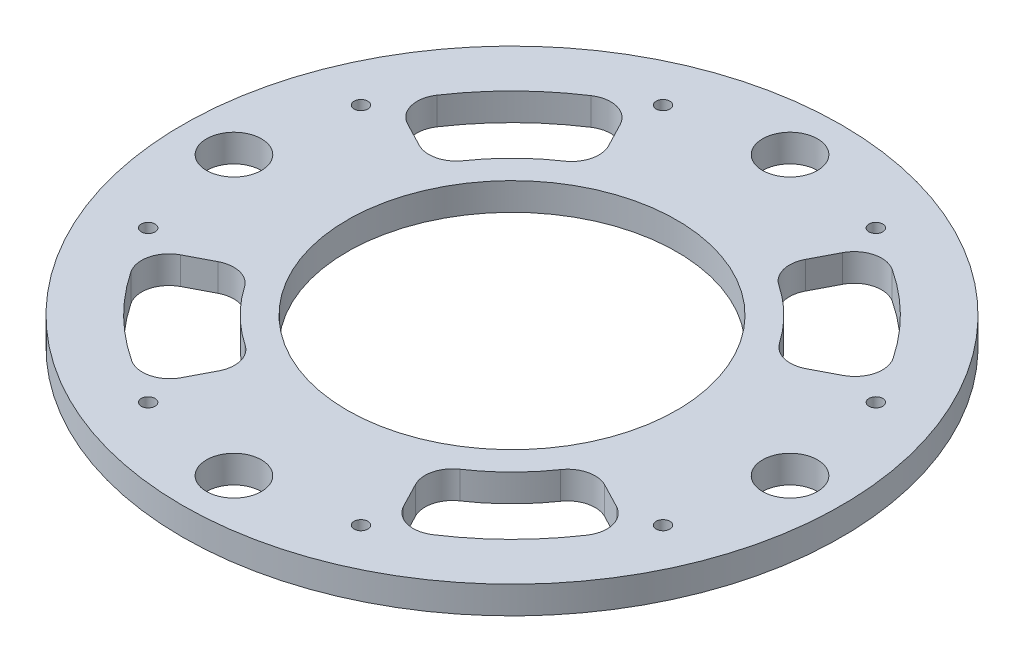
SolidWorks part; units mm, degrees
material "Acrylic (Medium-high impact)"
ref_plane "Front Plane" through (0, 0, 0) normal (0, 0, 1) x (1, 0, 0)
ref_plane "Top Plane" through (0, 0, 0) normal (0, 1, 0) x (1, 0, 0)
ref_plane "Right Plane" through (0, 0, 0) normal (1, 0, 0) x (0, 0, -1)
sketch "Sketch1" plane through (0, 0, 0) normal (0, 1, 0) x (1, 0, 0)
  circle A0 centre (0, 0) radius 76.2
  dimension "D1" = 152.4
extrude "Boss-Extrude1" add sketch "Sketch1" along normal blind 6.35
sketch "Sketch2" plane through (0, 6.35, 0) normal (0, 1, 0) x (1, 0, 0)
  circle A0 centre (0, 0) radius 35
  dimension "D1" = 70
extrude "Cut-Extrude1" cut sketch "Sketch2" against normal blind 6.35
sketch "Sketch3" plane through (0, 6.35, 0) normal (0, 1, 0) x (1, 0, 0)
  line L0 (-76.2, 0) -> (76.2, 0) construction
  line L1 (-51.5875, 51.5875) -> (51.5875, 51.5875) construction
  line L2 (-51.5875, 51.5875) -> (-51.5875, -51.5875) construction
  line L3 (-51.5875, -51.5875) -> (51.5875, -51.5875) construction
  line L4 (51.5875, 51.5875) -> (51.5875, -51.5875) construction
  circle A0 centre (0, 0) radius 76.2 construction
  circle A1 centre (-64.2875, 0) radius 6.35
  circle A2 centre (64.2875, 0) radius 6.35
  dimension "D1" = 12.7
  dimension "D2" = 12.7
  dimension "D3" = 12.7
  dimension "D4" = 12.7
extrude "Cut-Extrude2" cut sketch "Sketch3" against normal blind 10
sketch "Sketch4" plane through (0, 6.35, 0) normal (0, 1, 0) x (1, 0, 0)
  line L1 (50, -50) -> (-50, -50) construction
  line L2 (50, -50) -> (50, 50) construction
  line L3 (50, 50) -> (-50, 50) construction
  line L4 (-50, -50) -> (-50, 50) construction
  line L5 (50, -50) -> (-50, 50) construction
  line L6 (50, 50) -> (-50, -50) construction
  point P0 (0, 0)
  dimension "D1" = 100
  dimension "D2" = 100
sketch "Sketch5" plane through (0, 6.35, 0) normal (0, 1, 0) x (1, 0, 0)
  line L0 (-50, 24.6) -> (-59.525, 24.6) construction
  line L1 (-50, -50) -> (-50, 50) construction
  line L2 (-50, -24.6) -> (-59.525, -24.6) construction
  line L3 (50, 50) -> (-50, 50) construction
  line L4 (50, -50) -> (-50, -50) construction
  line L5 (-50, 50) -> (50, -50) construction
  line L6 (-50, -50) -> (50, 50) construction
  line L7 (24.6, 50) -> (24.6, 59.525) construction
  line L8 (-50, 50) -> (50, 50) construction
  line L9 (-50, 50) -> (-50, -50) construction
  line L10 (-50, -50) -> (50, -50) construction
  line L11 (50, 50) -> (50, -50) construction
  line L12 (-24.6, 50) -> (-24.6, 59.525) construction
  line L13 (50, 24.6) -> (59.525, 24.6) construction
  line L14 (-24.6, -50) -> (-24.6, -59.525) construction
  line L15 (24.6, -50) -> (24.6, -59.525) construction
  line L16 (50, -24.6) -> (59.525, -24.6) construction
  dimension "D1" = 25.4
  dimension "D2" = 25.4
  dimension "D3" = 9.525
  dimension "D4" = 9.525
sketch "Sketch7" plane through (0, 6.35, 0) normal (0, 1, 0) x (1, 0, 0)
  line L0 (0, 0) -> (0, 76.2) construction
  line L1 (0, 0) -> (53.8815, 53.8815) construction
  line L2 (0, 59.5249) -> (-24.5999, 59.5249) construction
  line L3 (0, 0) -> (76.2, 0) construction
  line L4 (0, -59.5249) -> (-24.5999, -59.5249) construction
  circle A0 centre (0, 0) radius 76.2 construction
  circle A1 centre (-24.5999, 59.5249) radius 1.5875
  circle A2 centre (24.5999, 59.5249) radius 1.5875
  circle A3 centre (24.5999, -59.5249) radius 1.5875
  circle A4 centre (-24.5999, -59.5249) radius 1.5875
  circle A5 centre (-59.5249, 24.5999) radius 1.5875
  circle A6 centre (-59.5249, -24.5999) radius 1.5875
  circle A7 centre (59.5249, 24.5999) radius 1.5875
  circle A8 centre (59.5249, -24.5999) radius 1.5875
  dimension "D1" = 45
  dimension "D2" = 59.5249
  dimension "D3" = 24.5999
extrude "Cut-Extrude4" cut sketch "Sketch7" against normal blind 10
sketch "Sketch8" plane through (0, 6.35, 0) normal (0, 1, 0) x (1, 0, 0)
  line L0 (0, 76.2) -> (0, -76.2) construction
  line L1 (0, 0) -> (53.8815, 53.8815) construction
  circle A0 centre (0, 0) radius 76.2 construction
  circle A1 centre (-64.2875, 0) radius 6.35
  circle A2 centre (64.2875, 0) radius 6.35
  circle A3 centre (0, -64.2875) radius 6.35
  circle A4 centre (0, 64.2875) radius 6.35
extrude "Cut-Extrude5" cut sketch "Sketch8" against normal blind 10
sketch "Sketch9" plane through (0, 6.35, 0) normal (0, 1, 0) x (1, 0, 0)
  circle A0 centre (0, 0) radius 38.1
  dimension "D1" = 76.2
extrude "Cut-Extrude6" cut sketch "Sketch9" against normal blind 10
sketch "Sketch10" plane through (0, 6.35, 0) normal (0, 1, 0) x (1, 0, 0)
  line L0 (0, 0) -> (-76.2, 0) construction
  line L1 (0, 0) -> (0, 76.2) construction
  line L2 (0, 0) -> (-53.8815, 53.8815) construction
  line L3 (-22.7447, 45.0673) -> (-25.6934, 50.7318)
  line L4 (-44.7067, 23.2729) -> (-50.3788, 26.2255)
  line L5 (44.7067, 23.2729) -> (50.3788, 26.2255)
  line L6 (22.7447, 45.0673) -> (25.6934, 50.7318)
  line L7 (22.7447, -45.0673) -> (25.6934, -50.7318)
  line L8 (44.7067, -23.2729) -> (50.3788, -26.2255)
  line L9 (-44.7067, -23.2729) -> (-50.3788, -26.2255)
  line L10 (-22.7447, -45.0673) -> (-25.6934, -50.7318)
  circle A0 centre (0, 0) radius 76.2 construction
  arc A1 (-24.83, 36.8683) -> (-36.5528, 25.2922) centre (0, 0) ccw
  arc A2 (-34.8066, 53.1108) -> (-52.7185, 35.3978) centre (0, 0) ccw
  circle A3 centre (0, 0) radius 38.1 construction
  arc A4 (-52.7185, 35.3978) -> (-50.3788, 26.2255) centre (-47.4467, 31.8581) ccw
  arc A5 (-44.7067, 23.2729) -> (-36.5528, 25.2922) centre (-41.7746, 28.9054) ccw
  arc A6 (-24.83, 36.8683) -> (-22.7447, 45.0673) centre (-28.3772, 42.1352) ccw
  arc A7 (-25.6934, 50.7318) -> (-34.8066, 53.1108) centre (-31.3259, 47.7997) ccw
  arc A8 (25.6934, 50.7318) -> (34.8066, 53.1108) centre (31.3259, 47.7997) cw
  arc A9 (24.83, 36.8683) -> (22.7447, 45.0673) centre (28.3772, 42.1352) cw
  arc A10 (44.7067, 23.2729) -> (36.5528, 25.2922) centre (41.7746, 28.9054) cw
  arc A11 (52.7185, 35.3978) -> (50.3788, 26.2255) centre (47.4467, 31.8581) cw
  arc A12 (34.8066, 53.1108) -> (52.7185, 35.3978) centre (0, 0) cw
  arc A13 (24.83, 36.8683) -> (36.5528, 25.2922) centre (0, 0) cw
  arc A14 (24.83, -36.8683) -> (36.5528, -25.2922) centre (0, 0) ccw
  arc A15 (34.8066, -53.1108) -> (52.7185, -35.3978) centre (0, 0) ccw
  arc A16 (52.7185, -35.3978) -> (50.3788, -26.2255) centre (47.4467, -31.8581) ccw
  arc A17 (44.7067, -23.2729) -> (36.5528, -25.2922) centre (41.7746, -28.9054) ccw
  arc A18 (24.83, -36.8683) -> (22.7447, -45.0673) centre (28.3772, -42.1352) ccw
  arc A19 (25.6934, -50.7318) -> (34.8066, -53.1108) centre (31.3259, -47.7997) ccw
  arc A20 (-25.6934, -50.7318) -> (-34.8066, -53.1108) centre (-31.3259, -47.7997) cw
  arc A21 (-24.83, -36.8683) -> (-22.7447, -45.0673) centre (-28.3772, -42.1352) cw
  arc A22 (-44.7067, -23.2729) -> (-36.5528, -25.2922) centre (-41.7746, -28.9054) cw
  arc A23 (-52.7185, -35.3978) -> (-50.3788, -26.2255) centre (-47.4467, -31.8581) cw
  arc A24 (-34.8066, -53.1108) -> (-52.7185, -35.3978) centre (0, 0) cw
  arc A25 (-24.83, -36.8683) -> (-36.5528, -25.2922) centre (0, 0) cw
  circle A26 centre (0, 0) radius 76.2
  dimension "D4" = 6.35
  dimension "D5" = 152.4
  dimension "D6" = 6.35
  dimension "D7" = 12.7
  dimension "D1" = 45
  dimension "D2" = 27.5
  dimension "D3" = 27.5
extrude "Cut-Extrude10" cut sketch "Sketch10" against normal blind 10 contours L3 A7 A2 A4 L4 A5 A1 A6 | A9 A13 A10 L5 A11 A12 A8 L6 | L7 A19 A15 A16 L8 A17 A14 A18 | A21 A25 A22 L9 A23 A24 A20 L10
sketch "Sketch11" plane through (0, 6.35, 0) normal (0, 1, 0) x (1, 0, 0)
  line L0 (-25.6934, 50.7318) -> (-22.7447, 45.0673)
  line L1 (-44.7067, 23.2729) -> (-50.3788, 26.2255)
  line L4 (44.7067, 23.2729) -> (50.3788, 26.2255)
  line L5 (25.6934, 50.7318) -> (22.7447, 45.0673)
  line L6 (25.6934, -50.7318) -> (22.7447, -45.0673)
  line L7 (44.7067, -23.2729) -> (50.3788, -26.2255)
  line L8 (-44.7067, -23.2729) -> (-50.3788, -26.2255)
  line L9 (-25.6934, -50.7318) -> (-22.7447, -45.0673)
  circle A0 centre (0, 0) radius 38.1
  circle A1 centre (0, 0) radius 76.2
  arc A2 (-24.83, 36.8683) -> (-36.5528, 25.2922) centre (0, 0) ccw
  arc A3 (34.8066, 53.1108) -> (52.7185, 35.3978) centre (0, 0) cw
  circle A4 centre (0, 64.2875) radius 6.5947
  circle A5 centre (-64.2875, 0) radius 6.35
  circle A6 centre (-59.5249, 24.5999) radius 1.5875
  circle A7 centre (-24.5999, 59.5249) radius 1.5875
  arc A8 (-50.3788, 26.2255) -> (-52.7185, 35.3978) centre (-47.4467, 31.8581) cw
  arc A9 (-44.7067, 23.2729) -> (-36.5528, 25.2922) centre (-41.7746, 28.9054) ccw
  arc A10 (-22.7447, 45.0673) -> (-24.83, 36.8683) centre (-28.3772, 42.1352) cw
  arc A11 (-25.6934, 50.7318) -> (-34.8066, 53.1108) centre (-31.3259, 47.7997) ccw
  arc A12 (-34.8066, 53.1108) -> (-52.7185, 35.3978) centre (0, 0) ccw
  arc A13 (25.6934, 50.7318) -> (34.8066, 53.1108) centre (31.3259, 47.7997) cw
  arc A14 (22.7447, 45.0673) -> (24.83, 36.8683) centre (28.3772, 42.1352) ccw
  arc A15 (44.7067, 23.2729) -> (36.5528, 25.2922) centre (41.7746, 28.9054) cw
  arc A16 (50.3788, 26.2255) -> (52.7185, 35.3978) centre (47.4467, 31.8581) ccw
  circle A17 centre (24.5999, 59.5249) radius 1.5875
  circle A18 centre (59.5249, 24.5999) radius 1.5875
  circle A19 centre (64.2875, 0) radius 6.35
  arc A20 (24.83, 36.8683) -> (36.5528, 25.2922) centre (0, 0) cw
  arc A21 (24.83, -36.8683) -> (36.5528, -25.2922) centre (0, 0) ccw
  circle A22 centre (59.5249, -24.5999) radius 1.5875
  circle A23 centre (24.5999, -59.5249) radius 1.5875
  arc A24 (50.3788, -26.2255) -> (52.7185, -35.3978) centre (47.4467, -31.8581) cw
  arc A25 (44.7067, -23.2729) -> (36.5528, -25.2922) centre (41.7746, -28.9054) ccw
  arc A26 (22.7447, -45.0673) -> (24.83, -36.8683) centre (28.3772, -42.1352) cw
  arc A27 (25.6934, -50.7318) -> (34.8066, -53.1108) centre (31.3259, -47.7997) ccw
  arc A28 (34.8066, -53.1108) -> (52.7185, -35.3978) centre (0, 0) ccw
  arc A29 (-34.8066, -53.1108) -> (-52.7185, -35.3978) centre (0, 0) cw
  arc A30 (-25.6934, -50.7318) -> (-34.8066, -53.1108) centre (-31.3259, -47.7997) cw
  arc A31 (-22.7447, -45.0673) -> (-24.83, -36.8683) centre (-28.3772, -42.1352) ccw
  arc A32 (-44.7067, -23.2729) -> (-36.5528, -25.2922) centre (-41.7746, -28.9054) cw
  arc A33 (-50.3788, -26.2255) -> (-52.7185, -35.3978) centre (-47.4467, -31.8581) ccw
  circle A34 centre (-24.5999, -59.5249) radius 1.5875
  circle A35 centre (-59.5249, -24.5999) radius 1.5875
  arc A36 (-24.83, -36.8683) -> (-36.5528, -25.2922) centre (0, 0) cw
  circle A37 centre (0, -64.2875) radius 6.35
